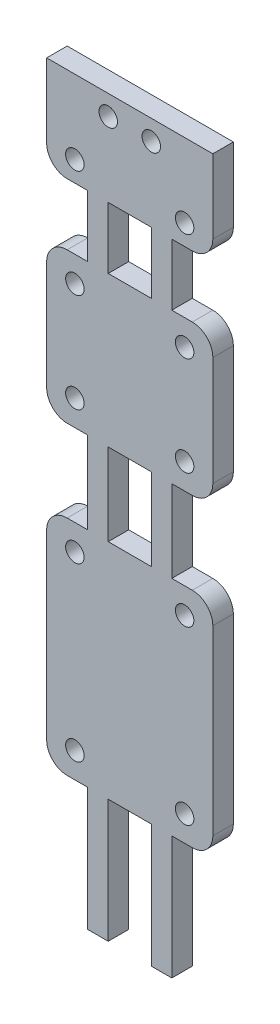
SolidWorks part; units mm, degrees
ref_plane "Front Plane" through (0, 0, 0) normal (0, 0, 1) x (1, 0, 0)
ref_plane "Top Plane" through (0, 0, 0) normal (0, 1, 0) x (1, 0, 0)
ref_plane "Right Plane" through (0, 0, 0) normal (1, 0, 0) x (0, 0, -1)
sketch "Sketch1" plane through (0, 0, 0) normal (0, 0, 1) x (1, 0, 0)
  line L0 (0, 1.5) -> (0, 14) construction
  line L1 (16.2, 1.5) -> (16.2, 14) construction
  line L2 (2, 47.74) -> (4, 47.74)
  line L3 (0, 1.5) -> (16.2, 1.5) construction
  line L4 (0, 14) -> (4, 14) construction
  line L5 (2, 26) -> (4, 26)
  line L6 (16.2, 85.59) -> (0, 85.59)
  line L7 (2, 70.385) -> (4, 70.385)
  line L8 (2, 55.74) -> (4, 55.74)
  line L9 (0, 28) -> (0, 45.74)
  line L10 (2, 76.385) -> (4, 76.385)
  line L11 (16.2, 28) -> (16.2, 45.74)
  line L12 (16.2, 57.74) -> (16.2, 68.385)
  line L13 (0, 57.74) -> (0, 68.385)
  line L14 (16.2, 78.385) -> (16.2, 85.59)
  line L15 (0, 78.385) -> (0, 85.59)
  line L16 (6, 70.385) -> (6, 76.385)
  line L17 (4, 55.74) -> (4, 47.74)
  line L18 (4, 70.385) -> (4, 76.385)
  line L19 (6, 55.74) -> (6, 47.74)
  line L20 (4, 26) -> (4, 14)
  line L21 (6, 26) -> (6, 14)
  line L22 (8.1, 1.5) -> (8.1, 85.59) construction
  line L23 (10.2, 26) -> (10.2, 14)
  line L24 (12.2, 26) -> (12.2, 14)
  line L25 (10.2, 55.74) -> (10.2, 47.74)
  line L26 (12.2, 55.74) -> (12.2, 47.74)
  line L27 (10.2, 70.385) -> (10.2, 76.385)
  line L28 (12.2, 70.385) -> (12.2, 76.385)
  line L29 (6, 26) -> (10.2, 26)
  line L30 (6, 14) -> (10.2, 14) construction
  line L31 (12.2, 14) -> (16.2, 14) construction
  line L32 (12.2, 26) -> (14.2, 26)
  line L33 (12.2, 47.74) -> (14.2, 47.74)
  line L34 (6, 47.74) -> (10.2, 47.74)
  line L35 (12.2, 76.385) -> (14.2, 76.385)
  line L36 (6, 76.385) -> (10.2, 76.385)
  line L37 (6, 70.385) -> (10.2, 70.385)
  line L38 (12.2, 70.385) -> (14.2, 70.385)
  line L39 (12.2, 55.74) -> (14.2, 55.74)
  line L40 (6, 55.74) -> (10.2, 55.74)
  line L41 (4, 14) -> (6, 14)
  line L42 (10.2, 14) -> (12.2, 14)
  circle A0 centre (13.45, 45.24) radius 0.9
  circle A1 centre (2.75, 67.885) radius 0.9
  circle A2 centre (13.45, 58.24) radius 0.9
  circle A3 centre (13.45, 78.385) radius 0.9
  circle A4 centre (2.75, 28.5) radius 0.9
  circle A5 centre (2.75, 78.385) radius 0.9
  circle A6 centre (2.75, 58.24) radius 0.9
  circle A7 centre (2.85, 11.5) radius 0.9 construction
  circle A8 centre (13.35, 11.5) radius 0.9 construction
  circle A9 centre (13.35, 5.5) radius 0.9 construction
  circle A10 centre (2.85, 5.5) radius 0.9 construction
  circle A11 centre (6, 83.635) radius 0.9
  circle A12 centre (13.45, 28.5) radius 0.9
  circle A13 centre (13.45, 67.885) radius 0.9
  circle A14 centre (10.2, 83.635) radius 0.9
  circle A15 centre (2.75, 45.24) radius 0.9
  arc A16 (0, 28) -> (2, 26) centre (2, 28) ccw
  arc A17 (16.2, 28) -> (14.2, 26) centre (14.2, 28) cw
  arc A18 (16.2, 45.74) -> (14.2, 47.74) centre (14.2, 45.74) ccw
  arc A19 (0, 45.74) -> (2, 47.74) centre (2, 45.74) cw
  arc A20 (0, 57.74) -> (2, 55.74) centre (2, 57.74) ccw
  arc A21 (16.2, 57.74) -> (14.2, 55.74) centre (14.2, 57.74) cw
  arc A22 (0, 68.385) -> (2, 70.385) centre (2, 68.385) cw
  arc A23 (16.2, 68.385) -> (14.2, 70.385) centre (14.2, 68.385) ccw
  arc A24 (16.2, 78.385) -> (14.2, 76.385) centre (14.2, 78.385) cw
  arc A25 (2, 76.385) -> (0, 78.385) centre (2, 78.385) cw
  point P77 (0, 26)
  point P80 (16.2, 26)
  point P83 (16.2, 47.74)
  point P86 (0, 47.74)
  point P89 (0, 55.74)
  point P92 (16.2, 55.74)
  point P95 (0, 70.385)
  point P98 (16.2, 70.385)
  point P101 (16.2, 76.385)
  point P104 (0, 76.385)
  dimension "D40" = 2
  dimension "D41" = 1.8
  dimension "D1" = 4
  dimension "D2" = 4
  dimension "D3" = 6
  dimension "D4" = 6
  dimension "D5" = 2.5
  dimension "D6" = 12
  dimension "D7" = 2.85
  dimension "D8" = 2.85
  dimension "D9" = 2.85
  dimension "D10" = 16.2
  dimension "D11" = 21.74
  dimension "D12" = 2.75
  dimension "D13" = 2.75
  dimension "D14" = 2.75
  dimension "D15" = 2.75
  dimension "D16" = 2.5
  dimension "D17" = 2.5
  dimension "D18" = 2.5
  dimension "D19" = 2.5
  dimension "D20" = 8
  dimension "D21" = 14.645
  dimension "D22" = 2.75
  dimension "D23" = 2.75
  dimension "D24" = 2.5
  dimension "D25" = 2.5
  dimension "D26" = 2.5
  dimension "D27" = 2.5
  dimension "D28" = 2.75
  dimension "D29" = 2.75
  dimension "D30" = 6
  dimension "D31" = 9.205
  dimension "D32" = 2.75
  dimension "D33" = 6
  dimension "D34" = 2
  dimension "D35" = 7.25
  dimension "D36" = 2
  dimension "D37" = 7.25
  dimension "D38" = 6
  dimension "D39" = 2.75
extrude "Boss-Extrude1" add sketch "Sketch1" along normal blind 2
sketch "Sketch2" plane through (0, 0, 2) normal (0, 0, 1) x (1, 0, 0)
  line L0 (4, 76.385) -> (12.2, 76.385)
  line L1 (12.2, 76.385) -> (12.2, 70.385)
  line L2 (12.2, 70.385) -> (4, 70.385)
  line L3 (4, 70.385) -> (4, 76.385)
  line L4 (4, 55.74) -> (12.2, 55.74)
  line L5 (12.2, 55.74) -> (12.2, 47.74)
  line L6 (12.2, 47.74) -> (4, 47.74)
  line L7 (4, 47.74) -> (4, 55.74)
  line L8 (4, 26) -> (12.2, 26)
  line L9 (12.2, 26) -> (12.2, 14)
  line L10 (12.2, 14) -> (4, 14)
  line L11 (4, 14) -> (4, 26)
extrude "Cut-Extrude1" [suppressed] cut sketch "Sketch2" against normal up to surface (2 mm away)
equation "\"D11@Sketch1\"= \"HL@parametersSketch@prostheticParameters.SLDPRT\" * 0.204 - 4 - 12 'Pinky PIP Length"
equation "\"D21@Sketch1\"= \"HL@parametersSketch@prostheticParameters.SLDPRT\" * 0.117 - 4 - 3 'Pinky MIP Length"
equation "\"D31@Sketch1\"= \"HL@parametersSketch@prostheticParameters.SLDPRT\" * 0.093 - 3 - 5'Pinky DIP Length"
equation "\"D10@Sketch1\"= \"fingerWidth@parametersSketch@prostheticParameters.SLDPRT\"'Pinky Width"
equation "\"D41@Sketch1\"= 1.5 + \"tol1@parametersSketch@prostheticParameters.SLDPRT\""
